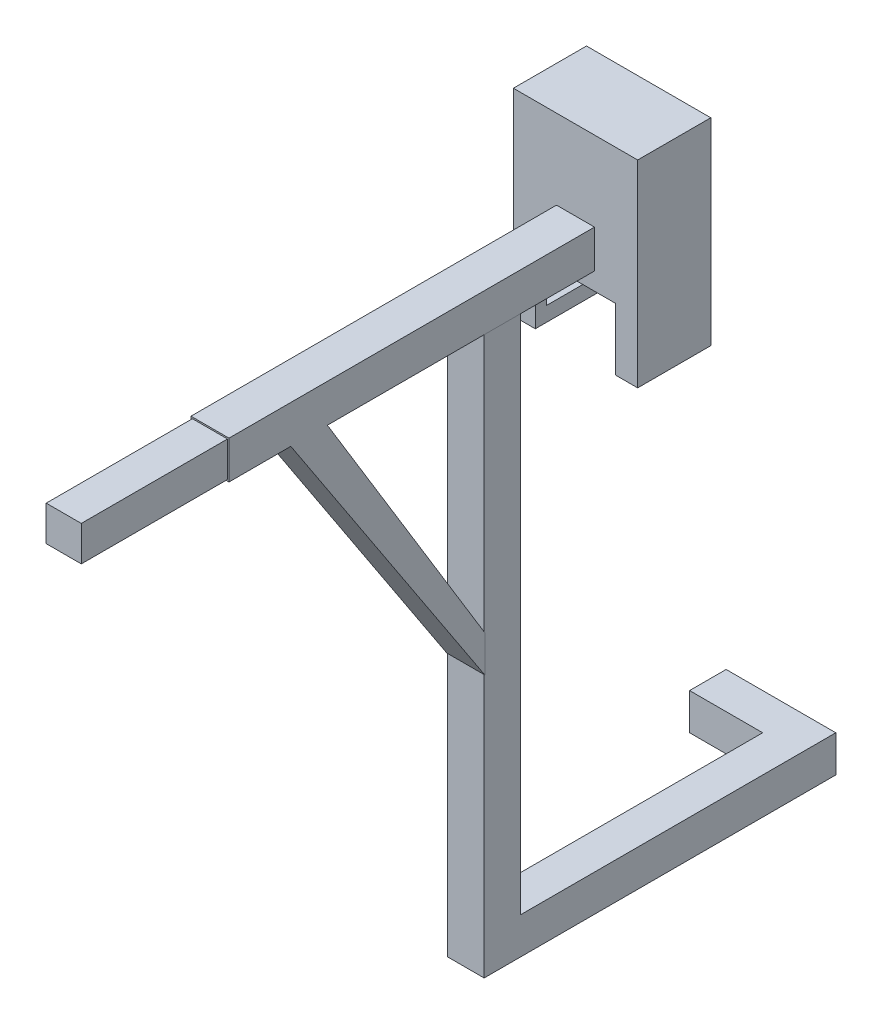
SolidWorks part; units mm, degrees
ref_plane "Front Plane" through (0, 0, 0) normal (0, 0, 1) x (1, 0, 0)
ref_plane "Top Plane" through (0, 0, 0) normal (0, 1, 0) x (1, 0, 0)
ref_plane "Right Plane" through (0, 0, 0) normal (1, 0, 0) x (0, 0, -1)
sketch "Sketch1" plane through (0, 0, 0) normal (0, 0, 1) x (1, 0, 0)
  line L1 (0, 0) -> (4.8, 0)
  line L2 (0, 0) -> (0, -4.8)
  line L3 (0, -4.8) -> (4.8, -4.8)
  line L4 (4.8, 0) -> (4.8, -4.8)
  dimension "D1" = 4.8
  dimension "D2" = 4.8
extrude "Boss-Extrude1" add sketch "Sketch1" along normal blind 20
sketch "Sketch2" plane through (0, 0, 0) normal (0, 0, -1) x (-1, 0, 0)
  line L0 (0, 0) -> (0, -4.8) construction
  line L1 (-5, 0.2) -> (0.2, 0.2)
  line L2 (-5, 0.2) -> (-5, -5)
  line L3 (-5, -5) -> (0.2, -5)
  line L4 (0.2, 0.2) -> (0.2, -5)
  line L5 (-5, 0.2) -> (0.2, -5) construction
  line L6 (-5, -5) -> (0.2, 0.2) construction
  line L7 (-4.8, 0) -> (0, 0) construction
  point P0 (-2.4, -2.4)
  dimension "D1" = 5.2
  dimension "D2" = 5.2
  dimension "D3" = 2.4
  dimension "D4" = 2.4
extrude "Boss-Extrude2" add sketch "Sketch2" along normal blind 50
sketch "Sketch3" plane through (0, 0, -50) normal (0, 0, -1) x (-1, 0, 0)
  line L0 (-5, -5) -> (0.2, -5) construction
  line L1 (-10.9, 11.1) -> (6.1, 11.1)
  line L2 (-10.9, 11.1) -> (-10.9, -15.9)
  line L3 (-10.9, -15.9) -> (6.1, -15.9)
  line L4 (6.1, 11.1) -> (6.1, -15.9)
  line L5 (-10.9, 11.1) -> (6.1, -15.9) construction
  line L6 (-10.9, -15.9) -> (6.1, 11.1) construction
  line L7 (0.2, -5) -> (0.2, 0.2) construction
  point P0 (-2.4, -2.4)
  dimension "D1" = 27
  dimension "D2" = 17
  dimension "D3" = 2.6
  dimension "D4" = 2.6
extrude "Boss-Extrude3" add sketch "Sketch3" along normal blind 10
sketch "Sketch4" plane through (0, 0, -60) normal (0, 0, -1) x (-1, 0, 0)
  line L0 (6.1, 11.1) -> (-10.9, 11.1) construction
  line L1 (4.1, 9.1) -> (-8.9, 9.1)
  line L2 (4.1, 9.1) -> (4.1, -13.9)
  line L3 (4.1, -13.9) -> (-8.9, -13.9)
  line L4 (-8.9, 9.1) -> (-8.9, -13.9)
  line L5 (4.1, 9.1) -> (-8.9, -13.9) construction
  line L6 (4.1, -13.9) -> (-8.9, 9.1) construction
  line L7 (6.1, -15.9) -> (6.1, 11.1) construction
  point P0 (-2.4, -2.4)
  dimension "D1" = 13
  dimension "D2" = 23
  dimension "D3" = 13.5
  dimension "D4" = 8.5
extrude "Cut-Extrude1" cut sketch "Sketch4" against normal blind 8.5
sketch "Sketch5" plane through (0, -15.9, 0) normal (0, -1, 0) x (1, 0, 0)
  line L0 (10.9, -50) -> (-6.1, -50) construction
  line L1 (-3.1, -50) -> (7.9, -50)
  line L2 (-3.1, -50) -> (-3.1, -58.5)
  line L3 (-3.1, -58.5) -> (7.9, -58.5)
  line L4 (7.9, -50) -> (7.9, -58.5)
  line L5 (10.9, -60) -> (-6.1, -60) construction
  line L6 (10.9, -60) -> (10.9, -50) construction
  line L7 (-6.1, -60) -> (-6.1, -50) construction
  point P10 (10.9, -55)
  dimension "D1" = 1.5
  dimension "D2" = 3
  dimension "D3" = 3
extrude "Cut-Extrude2" cut sketch "Sketch5" against normal blind 8.5
sketch "Sketch6" plane through (0, 0.2, 0) normal (0, 1, 0) x (1, 0, 0)
  line L0 (5, 50) -> (5, 0) construction
  line L1 (-0.1, 40) -> (4.9, 40)
  line L2 (-0.1, 40) -> (-0.1, 35)
  line L3 (-0.1, 35) -> (4.9, 35)
  line L4 (4.9, 40) -> (4.9, 35)
  line L5 (-0.1, 40) -> (4.9, 35) construction
  line L6 (-0.1, 35) -> (4.9, 40) construction
  line L7 (-0.2, 50) -> (5, 50) construction
  point P0 (2.4, 37.5)
  dimension "D1" = 5
  dimension "D2" = 5
  dimension "D3" = 2.6
  dimension "D4" = 10
extrude "Boss-Extrude4" add sketch "Sketch6" against normal blind 81.5
sketch "Sketch7" plane through (0, 0, -40) normal (0, 0, -1) x (-1, 0, 0)
  line L0 (0.1, -81.3) -> (0.1, -5) construction
  line L1 (-4.9, -81.3) -> (0.1, -81.3)
  line L2 (-4.9, -81.3) -> (-4.9, -76.3)
  line L3 (-4.9, -76.3) -> (0.1, -76.3)
  line L4 (0.1, -81.3) -> (0.1, -76.3)
  dimension "D1" = 5
  dimension "D2" = 5
extrude "Boss-Extrude5" add sketch "Sketch7" along normal blind 43.1
sketch "Sketch10" plane through (0, 0, -35) normal (0, 0, 1) x (1, 0, 0)
  line L0 (-0.1, -81.3) -> (-0.1, -5) construction
  line L1 (-0.1, -45.3599) -> (4.9, -45.3599)
  line L2 (-0.1, -45.3599) -> (-0.1, -40.3599)
  line L3 (-0.1, -40.3599) -> (4.9, -40.3599)
  line L4 (4.9, -45.3599) -> (4.9, -40.3599)
  line L5 (4.9, -81.3) -> (4.9, -5) construction
  dimension "D1" = 5
  dimension "D2" = 5
sketch "Sketch11" plane through (0, -5, 0) normal (0, -1, 0) x (1, 0, 0)
  line L0 (-0.2, -50) -> (-0.2, 0) construction
  line L1 (-0.2, -13.4558) -> (5, -13.4558)
  line L2 (-0.2, -13.4558) -> (-0.2, -8.4558)
  line L3 (-0.2, -8.4558) -> (5, -8.4558)
  line L4 (5, -13.4558) -> (5, -8.4558)
  line L5 (5, -50) -> (5, 0) construction
  dimension "D1" = 5
  dimension "D2" = 5.2
sketch "Sketch12" plane through (5, 0, 0) normal (1, 0, 0) x (0, 0, -1)
  line L0 (13.4558, -5) -> (35, -40.3599)
  line L1 (13.4558, -5) -> (8.4558, -5) construction
  line L2 (50, -5) -> (0, -5) construction
  line L3 (35, -45.3599) -> (35, -40.3599) construction
  line L4 (35, -45.3599) -> (35, -40.3599) construction
  line L5 (8.4558, -5) -> (35, -45.3599)
  line L6 (8.4558, -5) -> (13.4558, -5)
  line L7 (35, -40.3599) -> (35, -45.3599)
extrude "Boss-Extrude6" add sketch "Sketch12" against normal blind 5.2
sketch "Sketch13" plane through (-0.1, 0, 0) normal (-1, 0, 0) x (0, 0, 1)
  line L0 (-83.1, -76.3) -> (-40, -76.3) construction
  line L1 (-83.1, -81.3) -> (-78.1, -81.3)
  line L2 (-83.1, -81.3) -> (-83.1, -76.3)
  line L3 (-83.1, -76.3) -> (-78.1, -76.3)
  line L4 (-78.1, -81.3) -> (-78.1, -76.3)
  dimension "D1" = 5
extrude "Boss-Extrude7" add sketch "Sketch13" along normal blind 10
